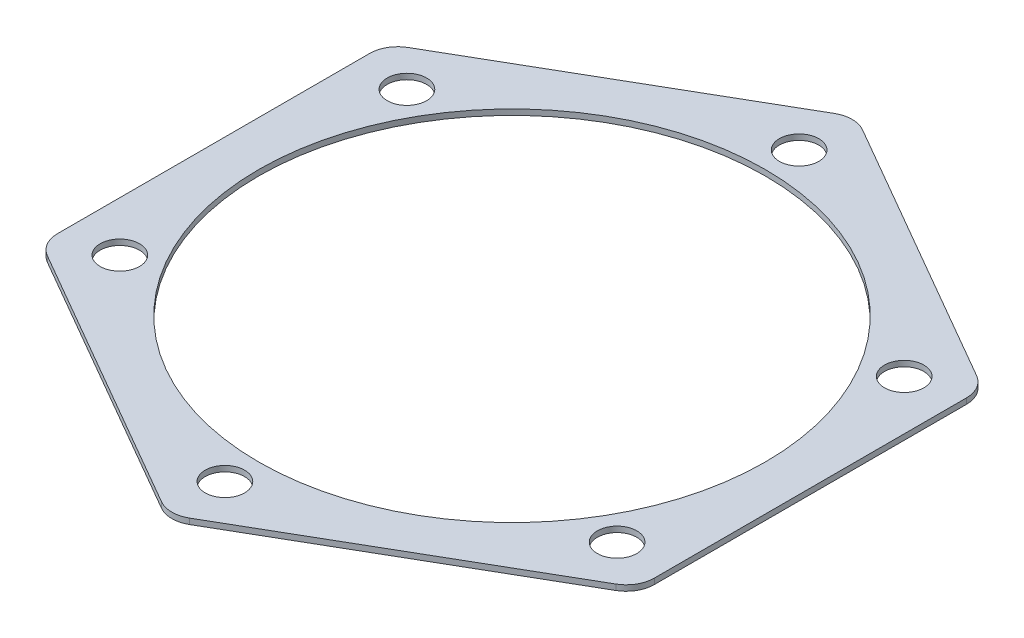
SolidWorks part; units mm, degrees
ref_plane "Front Plane" through (0, 0, 0) normal (0, 0, 1) x (1, 0, 0)
ref_plane "Top Plane" through (0, 0, 0) normal (0, 1, 0) x (1, 0, 0)
ref_plane "Right Plane" through (0, 0, 0) normal (1, 0, 0) x (0, 0, -1)
sketch "Sketch1" plane through (0, 0, 0) normal (0, 1, 0) x (1, 0, 0)
  line L1 (-50.5, -32.0429) -> (-2.5, -59.7558)
  line L2 (2.5, -59.7558) -> (50.5, -32.0429)
  line L3 (53, -27.7128) -> (53, 27.7128)
  line L4 (50.5, 32.0429) -> (2.5, 59.7558)
  line L5 (-2.5, 59.7558) -> (-50.5, 32.0429)
  line L6 (-53, 27.7128) -> (-53, -27.7128)
  circle A0 centre (0, 0) radius 53 construction
  circle A1 centre (0, 0) radius 51 construction
  circle A2 centre (0, 0) radius 45
  circle A3 centre (0, 51) radius 3.5
  circle A4 centre (44.1673, 25.5) radius 3.5
  circle A5 centre (44.1673, -25.5) radius 3.5
  circle A6 centre (0, -51) radius 3.5
  circle A7 centre (-44.1673, -25.5) radius 3.5
  circle A8 centre (-44.1673, 25.5) radius 3.5
  arc A9 (-50.5, 32.0429) -> (-53, 27.7128) centre (-48, 27.7128) ccw
  arc A10 (-50.5, -32.0429) -> (-53, -27.7128) centre (-48, -27.7128) cw
  arc A11 (-2.5, -59.7558) -> (2.5, -59.7558) centre (0, -55.4256) ccw
  arc A12 (50.5, -32.0429) -> (53, -27.7128) centre (48, -27.7128) ccw
  arc A13 (53, 27.7128) -> (50.5, 32.0429) centre (48, 27.7128) ccw
  arc A14 (2.5, 59.7558) -> (-2.5, 59.7558) centre (0, 55.4256) ccw
  point P26 (0, 0)
  point P37 (0, 61.1991)
  dimension "D2" = 102
  dimension "D3" = 90
  dimension "D4" = 7
  dimension "D6" = 5
  dimension "D1" = 106
  dimension "D5" = 6
extrude "Boss-Extrude1" add sketch "Sketch1" along normal blind 1
